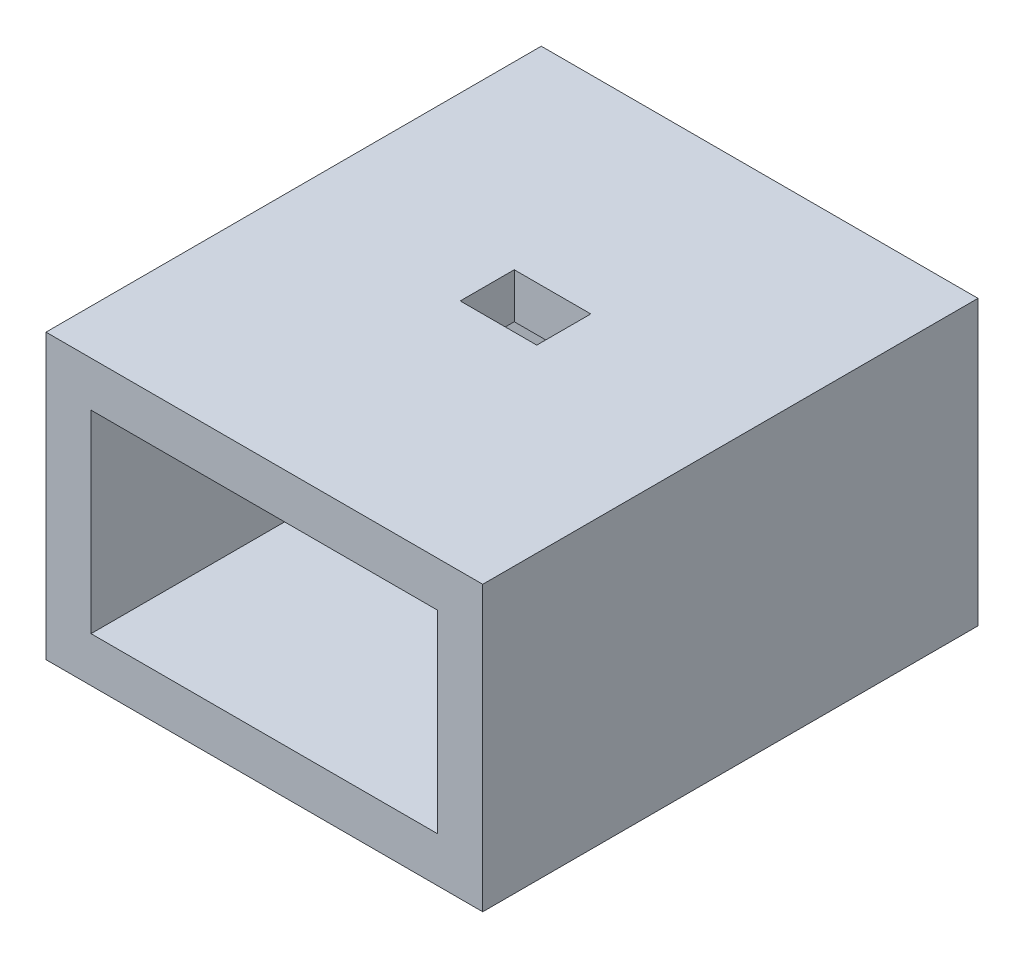
SolidWorks part; units mm, degrees
ref_plane "Plano frontal" through (0, 0, 0) normal (0, 0, 1) x (1, 0, 0)
ref_plane "Plano superior" through (0, 0, 0) normal (0, 1, 0) x (1, 0, 0)
ref_plane "Plano direito" through (0, 0, 0) normal (1, 0, 0) x (0, 0, -1)
sketch "Esboço1" plane through (0, 0, 0) normal (0, 0, 1) x (1, 0, 0)
  line L0 (4.85, -2.05) -> (-4.85, -2.05)
  line L2 (-4.85, -2.05) -> (-4.85, 4.25)
  line L3 (-4.85, 4.25) -> (4.85, 4.25)
  line L4 (4.85, -2.05) -> (4.85, 4.25)
  dimension "D1" = 9.7
  dimension "D2" = 6.3
extrude "Ressalto-extrusão1" add sketch "Esboço1" along normal blind 11
sketch "Esboço5" plane through (0, 0, 11) normal (0, 0, 1) x (1, 0, 0)
  line L0 (3.85, -1.05) -> (-3.85, -1.05)
  line L1 (-4.85, -2.05) -> (4.85, -2.05) construction
  line L2 (4.85, 4.25) -> (-4.85, 4.25) construction
  line L3 (4.85, -2.05) -> (4.85, 4.25) construction
  line L4 (-3.85, -1.05) -> (-3.85, 3.25)
  line L5 (-3.85, 3.25) -> (3.85, 3.25)
  line L6 (3.85, -1.05) -> (3.85, 3.25)
  line L7 (-4.85, 4.25) -> (-4.85, -2.05) construction
  dimension "D1" = 1
  dimension "D2" = 1
  dimension "D3" = 1
  dimension "D4" = 1
extrude "Corte-extrusão1" cut sketch "Esboço5" against normal blind 9
sketch "Esboço6" plane through (0, 4.25, 0) normal (0, 1, 0) x (1, 0, 0)
  line L0 (0, 0) -> (0, -11) construction
  line L1 (-0.85, -4.6) -> (0.85, -4.6)
  line L2 (-0.85, -4.6) -> (-0.85, -5.8)
  line L3 (-0.85, -5.8) -> (0.85, -5.8)
  line L4 (0.85, -4.6) -> (0.85, -5.8)
  line L5 (-0.85, -4.6) -> (0.85, -5.8) construction
  line L6 (-0.85, -5.8) -> (0.85, -4.6) construction
  line L7 (4.85, 0) -> (-4.85, 0) construction
  line L8 (4.85, -11) -> (-4.85, -11) construction
  point P0 (0, -5.2)
  dimension "D1" = 1.7
  dimension "D2" = 1.2
  dimension "D3" = 5.2
extrude "Corte-extrusão2" cut sketch "Esboço6" against normal blind 2
